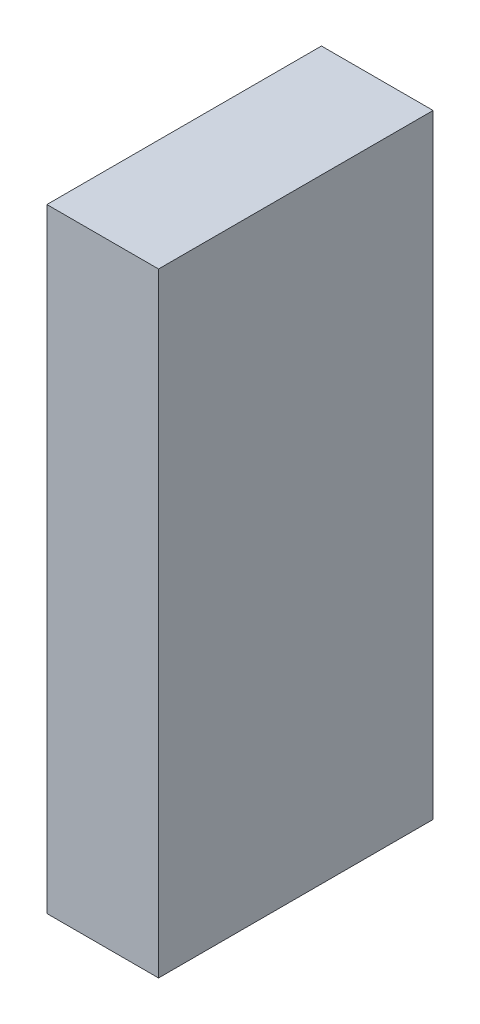
SolidWorks part; units mm, degrees
ref_plane "Front Plane" through (0, 0, 0) normal (0, 0, 1) x (1, 0, 0)
ref_plane "Top Plane" through (0, 0, 0) normal (0, 1, 0) x (1, 0, 0)
ref_plane "Right Plane" through (0, 0, 0) normal (1, 0, 0) x (0, 0, -1)
sketch "Sketch1" plane through (0, 0, 0) normal (0, 1, 0) x (1, 0, 0)
  line L1 (-11.546, -28.3937) -> (11.546, -28.3937)
  line L2 (-11.546, -28.3937) -> (-11.546, 28.3937)
  line L3 (-11.546, 28.3937) -> (11.546, 28.3937)
  line L4 (11.546, -28.3937) -> (11.546, 28.3937)
  line L5 (-11.546, -28.3937) -> (11.546, 28.3937) construction
  line L6 (-11.546, 28.3937) -> (11.546, -28.3937) construction
  point P0 (0, 0)
extrude "Boss-Extrude1" add sketch "Sketch1" along normal blind 127
